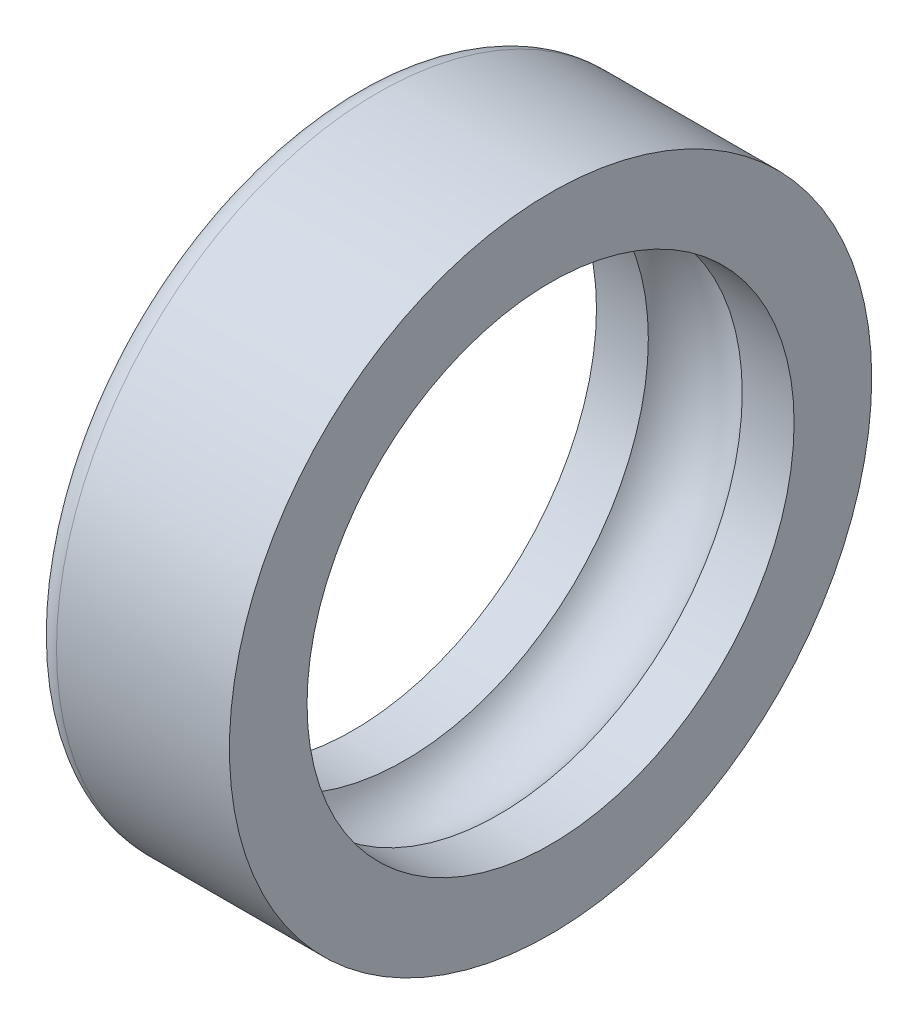
SolidWorks part; units mm, degrees
ref_plane "Front Plane" through (0, 0, 0) normal (0, 0, 1) x (1, 0, 0)
ref_plane "Top Plane" through (0, 0, 0) normal (0, 1, 0) x (1, 0, 0)
ref_plane "Right Plane" through (0, 0, 0) normal (1, 0, 0) x (0, 0, -1)
sketch "Sketch1" plane through (0, 0, 0) normal (0, 0, 1) x (1, 0, 0)
  line L0 (0, 0) -> (13.3111, 0) construction
  line L1 (13.3111, 0) -> (13.3111, 1.108) construction
  line L2 (0, 0) -> (0, 4.25) construction
  line L3 (0, 4.25) -> (4, 4.25)
  line L4 (0, 4.25) -> (-4, 4.25)
  line L5 (4, 4.25) -> (4, 1.108)
  line L6 (-4, 4.25) -> (-4, 1.108)
  line L7 (-4, 1.108) -> (-1.9006, 1.108)
  line L8 (4, 1.108) -> (1.9006, 1.108)
  line L9 (4, 4.25) -> (4, -8.75) construction
  line L10 (4, -8.75) -> (-4, -8.75) construction
  arc A0 (1.9006, 1.108) -> (-1.9006, 1.108) centre (0, 0) ccw
  dimension "D1" = 4.4
  dimension "D2" = 1.108
  dimension "D3" = 4.25
  dimension "D4" = 4
  dimension "D5" = 4
  dimension "D6" = 3.142
  dimension "D7" = 13
revolve "Revolve1" add sketch "Sketch1" angle 360 about L10
fillet "Fillet1" radius 1 1 edges at (-4, -8.75, -13)
